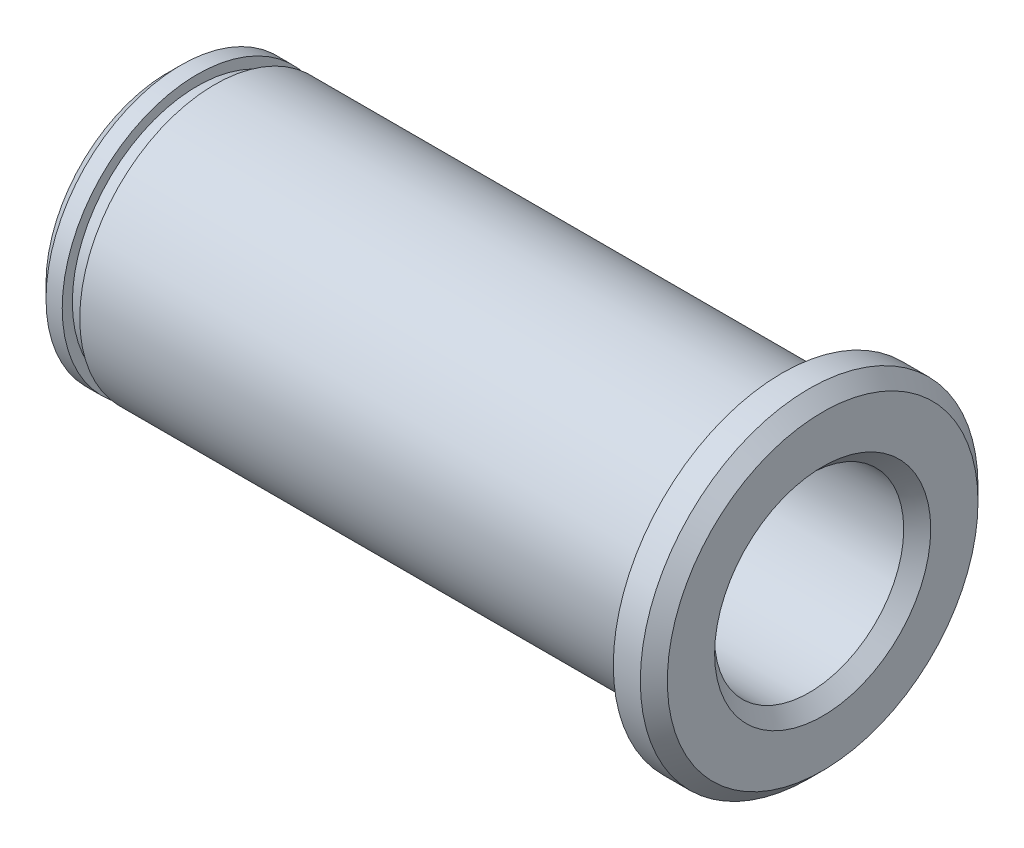
SolidWorks part; units mm, degrees
material "AISI 4340 Steel, annealed"
ref_plane "Front Plane" through (0, 0, 0) normal (0, 0, 1) x (1, 0, 0)
ref_plane "Top Plane" through (0, 0, 0) normal (0, 1, 0) x (1, 0, 0)
ref_plane "Right Plane" through (0, 0, 0) normal (1, 0, 0) x (0, 0, -1)
sketch "Sketch1" plane through (0, 0, 0) normal (0, 0, 1) x (1, 0, 0)
  line L0 (0, 0) -> (49.6014, 0) construction
  line L1 (0, -7) -> (48.5, -7)
  line L2 (48.5, -7) -> (48.5, -12.5)
  line L3 (48.5, -12.5) -> (45.5, -12.5)
  line L4 (45.5, -12.5) -> (45.5, -10)
  line L5 (45.5, -10) -> (3.5, -10)
  line L6 (3.5, -10) -> (3.5, -9.25)
  line L7 (3.5, -9.25) -> (2.2, -9.25)
  line L8 (2.2, -9.25) -> (2.2, -10)
  line L9 (2.2, -10) -> (0, -10)
  line L10 (0, -10) -> (0, -7)
  dimension "D1" = 42
  dimension "D2" = 10
  dimension "D3" = 3
  dimension "D4" = 12.5
  dimension "D5" = 48.5
  dimension "D6" = 1.3
  dimension "D7" = 3
  dimension "D8" = 18.5
revolve "Revolve1" add sketch "Sketch1" angle 360 about L0
chamfer "Chamfer1" distance 1 angle 45 4 edges at (0, 0, 10) (48.5, 0, 12.5) (0, 0, 7) (48.5, 0, 7)
fillet "Fillet1" radius 0.5 1 edges at (45.5, 0, 10)
